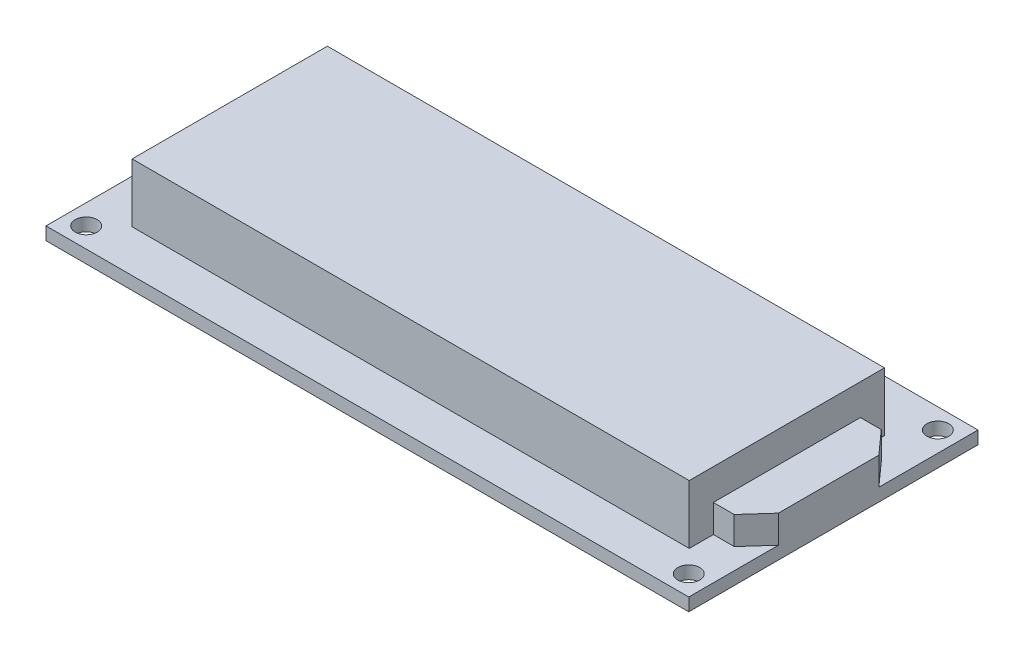
SolidWorks part; units mm, degrees
ref_plane "Front Plane" through (0, 0, 0) normal (0, 0, 1) x (1, 0, 0)
ref_plane "Top Plane" through (0, 0, 0) normal (0, 1, 0) x (1, 0, 0)
ref_plane "Right Plane" through (0, 0, 0) normal (1, 0, 0) x (0, 0, -1)
sketch "Sketch1" plane through (0, 0, 0) normal (0, 1, 0) x (1, 0, 0)
  line L1 (40, 18) -> (-40, 18)
  line L2 (40, 18) -> (40, -18)
  line L3 (40, -18) -> (-40, -18)
  line L4 (-40, 18) -> (-40, -18)
  line L5 (40, 18) -> (-40, -18) construction
  line L6 (40, -18) -> (-40, 18) construction
  point P0 (0, 0)
  dimension "D1" = 80
  dimension "D2" = 36
extrude "Boss-Extrude1" add sketch "Sketch1" along normal blind 1.6
sketch "Sketch2" plane through (0, 1.6, 0) normal (0, 1, 0) x (1, 0, 0)
  line L0 (-40, 18) -> (-40, -18) construction
  line L1 (-34.54, 11.56) -> (34.8, 11.56)
  line L2 (-34.54, 11.56) -> (-34.54, -12.74)
  line L3 (-34.54, -12.74) -> (34.8, -12.74)
  line L4 (34.8, 11.56) -> (34.8, -12.74)
  line L5 (-34.54, 11.56) -> (34.8, -12.74) construction
  line L6 (-34.54, -12.74) -> (34.8, 11.56) construction
  line L7 (40, -18) -> (40, 18) construction
  line L8 (40, 18) -> (-40, 18) construction
  line L9 (-40, -18) -> (40, -18) construction
  point P0 (0.13, -0.59)
  dimension "D1" = 69.34
  dimension "D2" = 24.3
  dimension "D3" = 5.46
  dimension "D4" = 5.2
  dimension "D5" = 6.44
  dimension "D6" = 5.26
extrude "Boss-Extrude2" add sketch "Sketch2" along normal blind 7.32
sketch "Sketch3" plane through (0, 1.6, 0) normal (0, 1, 0) x (1, 0, 0)
  line L1 (34.8, -12.74) -> (34.8, 11.56) construction
  line L2 (40, 5.66) -> (40, -6.84)
  line L4 (34.8, -12.74) -> (34.8, 11.56) construction
  line L5 (34.8, -9.74) -> (34.8, 8.56)
  line L6 (40, -18) -> (40, 18) construction
  line L7 (34.8, 8.56) -> (37.4, 8.56)
  line L8 (37.4, 8.56) -> (40, 5.66)
  line L9 (40, -6.84) -> (37.4, -9.74)
  line L10 (37.4, -9.74) -> (34.8, -9.74)
  line L11 (-34.54, -0.59) -> (51.0871, -0.59) construction
  line L12 (-34.54, 11.56) -> (-34.54, -12.74) construction
  dimension "D1" = 18.3
  dimension "D2" = 12.5
  dimension "D3" = 2.6
extrude "Boss-Extrude3" add sketch "Sketch3" along normal blind 3.46
sketch "Sketch4" plane through (0, 1.6, 0) normal (0, 1, 0) x (1, 0, 0)
  line L0 (0, 0) -> (0, 18) construction
  line L1 (40, 18) -> (-40, 18) construction
  line L2 (0, 0) -> (-40, 0) construction
  line L3 (-40, 18) -> (-40, -18) construction
  line L4 (-40, -18) -> (40, -18) construction
  circle A0 centre (-37.5, 15.5) radius 1.36
  circle A1 centre (-37.5, -15.5) radius 1.36
  circle A2 centre (37.5, -15.5) radius 1.36
  circle A3 centre (37.5, 15.5) radius 1.36
  point P16 (0, 0)
  point P17 (0, 0)
  point P18 (0, 0)
  point P19 (0, 0)
  dimension "D3" = 2.72
  dimension "D1" = 2.5
  dimension "D2" = 2.5
extrude "Cut-Extrude1" cut sketch "Sketch4" against normal through all both and the other way through all
